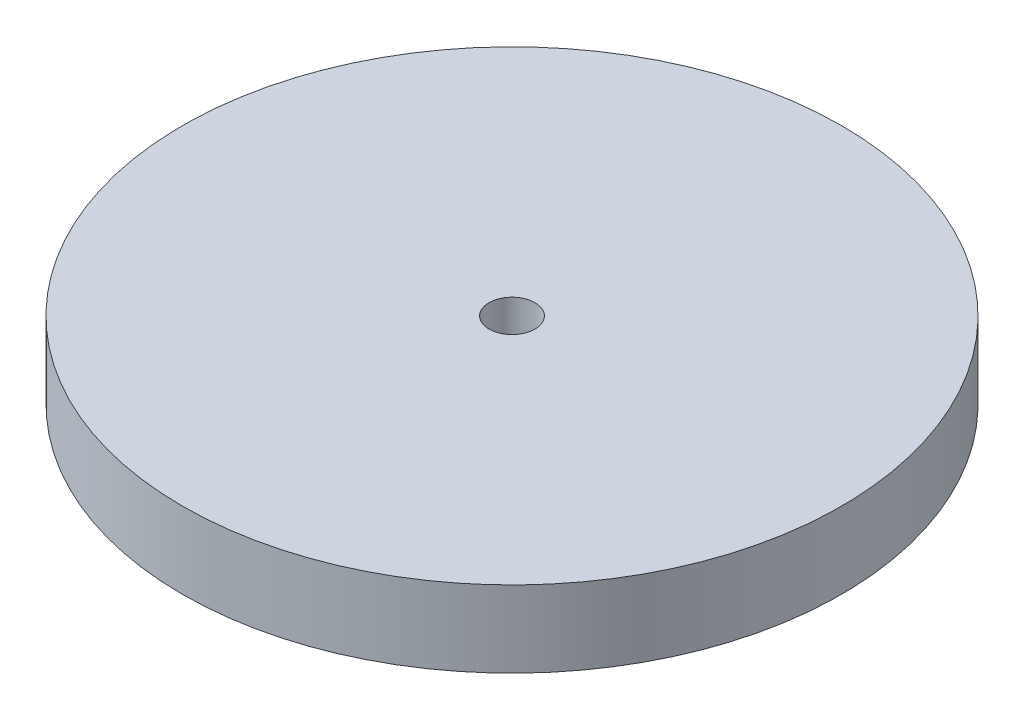
SolidWorks part; units mm, degrees
ref_plane "Front Plane" through (0, 0, 0) normal (0, 0, 1) x (1, 0, 0)
ref_plane "Top Plane" through (0, 0, 0) normal (0, 1, 0) x (1, 0, 0)
ref_plane "Right Plane" through (0, 0, 0) normal (1, 0, 0) x (0, 0, -1)
sketch "Sketch1" plane through (0, 0, 0) normal (0, 1, 0) x (1, 0, 0)
  circle A0 centre (0, 0) radius 34.5
  circle A1 centre (0, 0) radius 2.4
  dimension "D1" = 69
  dimension "D2" = 4.8
extrude "Boss-Extrude1" add sketch "Sketch1" along normal blind 8
